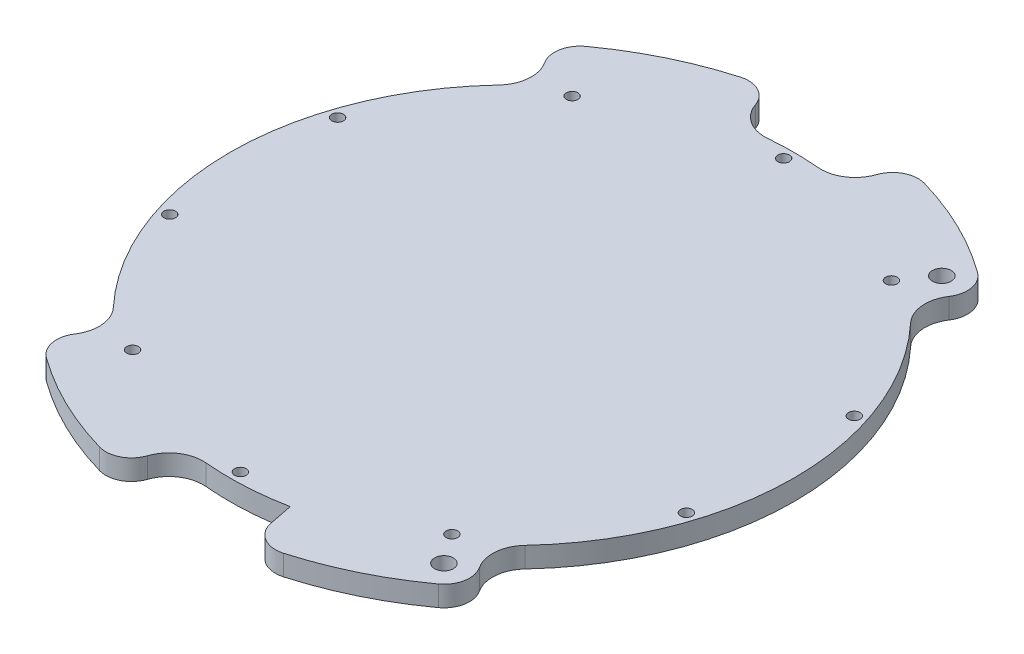
SolidWorks part; units mm, degrees
material "Acrylic (Medium-high impact)"
ref_plane "Front Plane" through (0, 0, 0) normal (0, 0, 1) x (1, 0, 0)
ref_plane "Top Plane" through (0, 0, 0) normal (0, 1, 0) x (1, 0, 0)
ref_plane "Right Plane" through (0, 0, 0) normal (1, 0, 0) x (0, 0, -1)
sketch "Sketch1" plane through (0, 0, 0) normal (0, 1, 0) x (1, 0, 0)
  line L0 (0, 0) -> (0, 79.5) construction
  line L1 (0, 0) -> (46.7289, 64.3169) construction
  line L4 (0, 0) -> (-52.9347, 72.8584) construction
  line L5 (-1000, 0) -> (49000, 0) construction
  line L7 (-58.6141, 67.96) -> (0, 0) construction
  line L9 (-58.6141, -67.96) -> (0, 0) construction
  line L11 (-58.6141, 67.96) -> (-53.9149, 62.5115)
  line L12 (-58.6141, -67.96) -> (-53.9149, -62.5115)
  line L14 (-52.9347, 72.8584) -> (-57.3431, 78.926) construction
  line L15 (0, 0) -> (-26.8906, 93.7786) construction
  line L16 (-42.7666, 87.6844) -> (0, 0) construction
  line L17 (-17.4667, 88.0289) -> (-16.0664, 80.9714)
  line L18 (-17.4667, -88.0289) -> (-16.0664, -80.9714)
  line L19 (17.4667, -88.0289) -> (16.0664, -80.9714)
  line L20 (58.6141, -67.96) -> (53.9149, -62.5115)
  line L21 (58.6141, 67.96) -> (53.9149, 62.5115)
  line L22 (17.4667, 88.0289) -> (16.0664, 80.9714)
  line L23 (0, -1000) -> (0, 49000) construction
  line L24 (52.9347, 72.8584) -> (0, 0) construction
  arc A0 (0, 79.5) -> (-51.9229, -60.2019) centre (0, 0) ccw construction
  arc A1 (-53.9149, 62.5115) -> (-53.9149, -62.5115) centre (0, 0) ccw
  arc A4 (-58.6141, 67.96) -> (-57.3431, 78.926) centre (-52.9347, 72.8584) cw
  arc A5 (-58.6141, -67.96) -> (-57.3431, -78.926) centre (-52.9347, -72.8584) ccw
  arc A6 (-16.0664, -80.9714) -> (16.0664, -80.9714) centre (0, 0) ccw
  arc A8 (-57.3431, 78.926) -> (-26.8906, 93.7786) centre (0, 0) cw
  arc A9 (-17.4667, 88.0289) -> (-26.8906, 93.7786) centre (-24.8233, 86.5692) ccw
  arc A10 (-17.4667, -88.0289) -> (-26.8906, -93.7786) centre (-24.8233, -86.5692) cw
  arc A11 (-57.3431, -78.926) -> (-26.8906, -93.7786) centre (0, 0) ccw
  arc A12 (17.4667, -88.0289) -> (26.8906, -93.7786) centre (24.8233, -86.5692) ccw
  arc A13 (57.3431, -78.926) -> (26.8906, -93.7786) centre (0, 0) cw
  arc A14 (58.6141, -67.96) -> (57.3431, -78.926) centre (52.9347, -72.8584) cw
  arc A15 (58.6141, 67.96) -> (57.3431, 78.926) centre (52.9347, 72.8584) ccw
  arc A16 (57.3431, 78.926) -> (26.8906, 93.7786) centre (0, 0) ccw
  arc A17 (17.4667, 88.0289) -> (26.8906, 93.7786) centre (24.8233, 86.5692) cw
  arc A18 (16.0664, 80.9714) -> (-16.0664, 80.9714) centre (0, 0) ccw
  arc A19 (79.5, 0) -> (46.7289, 64.3169) centre (0, 0) ccw construction
  arc A20 (53.9149, -62.5115) -> (53.9149, 62.5115) centre (0, 0) ccw
  circle A21 centre (52.9347, -72.8584) radius 2.75
  circle A22 centre (52.9347, 72.8584) radius 2.75
  circle A23 centre (0, 0) radius 90.0579 construction
  point P4 (0, 79.5)
  point P5 (46.7289, 64.3169)
  point P8 (75.609, 24.5669)
  point P9 (75.609, -24.5669)
  point P10 (46.7289, -64.3169)
  point P11 (0, -79.5)
  point P12 (-46.7289, -64.3169)
  point P13 (-75.609, -24.5669)
  point P14 (-75.609, 24.5669)
  point P15 (-46.7289, 64.3169)
  point P16 (0, 0)
  dimension "D1" = 159
  dimension "D2" = 165.1
  dimension "D5" = 7.5
  dimension "D6" = 5.5
  dimension "D7" = 20
  dimension "D8" = 97.5579
  dimension "D4" = 36
  dimension "D3" = 10
extrude "Boss-Extrude1" add sketch "Sketch1" along normal mid plane 6
hole_wizard "M3 Clearance Hole1" positions "Sketch2" profile "Sketch3" hole size "M3" standard "ANSI Metric" end condition through all
sketch "Sketch2" plane through (0, 3, 0) normal (0, 1, 0) x (1, 0, 0)
  point P0 (0, 79.5)
  point P3 (46.7289, 64.3169)
  point P6 (75.609, 24.5669)
  point P9 (75.609, -24.5669)
  point P12 (46.7289, -64.3169)
  point P15 (0, -79.5)
  point P18 (-46.7289, -64.3169)
  point P21 (-75.609, -24.5669)
  point P24 (-75.609, 24.5669)
  point P27 (-46.7289, 64.3169)
sketch "Sketch3" plane through (0, 3, -79.5) normal (1, 0, 0) x (0, 0, 1)
  line L0 (0, 0) -> (0, 6)
  line L1 (0, 6) -> (1.7, 6)
  line L2 (1.7, 6) -> (1.7, 0)
  line L5 (1.7, 0) -> (0, 0)
  line L11 (0, -6.35) -> (0, 107.95) construction
  dimension "Thru Hole Dia." = 3.4
  dimension "Thru Hole Depth" = 6
fillet "Fillet2" radius 10 7 edges at (-53.9149, 0, 62.5115) (-53.9149, 0, -62.5115) (-16.0664, 0, 80.9714) (53.9149, 0, 62.5115) (53.9149, 0, -62.5115) (16.0664, 0, -80.9714) (-16.0664, 0, -80.9714)
